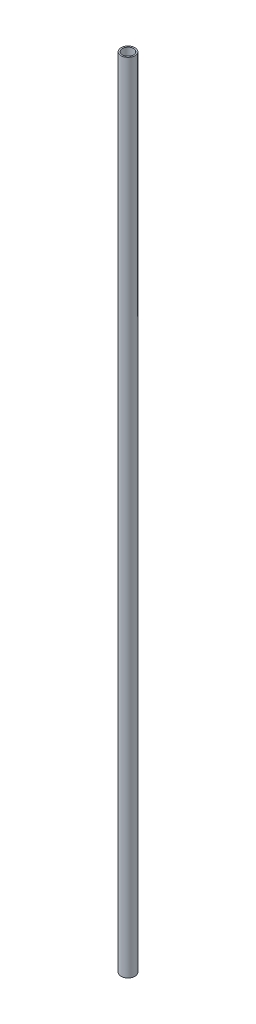
SolidWorks part; units mm, degrees
material "Thornel Mat VMA"
ref_plane "Front Plane" through (0, 0, 0) normal (0, 0, 1) x (1, 0, 0)
ref_plane "Top Plane" through (0, 0, 0) normal (0, 1, 0) x (1, 0, 0)
ref_plane "Right Plane" through (0, 0, 0) normal (1, 0, 0) x (0, 0, -1)
sketch "Sketch1" plane through (0, 0, 0) normal (0, 1, 0) x (1, 0, 0)
  circle A0 centre (0, 0) radius 2.5
  circle A1 centre (0, 0) radius 2
  dimension "D1" = 4
  dimension "D2" = 5
extrude "Boss-Extrude1" add sketch "Sketch1" along normal mid plane 287
